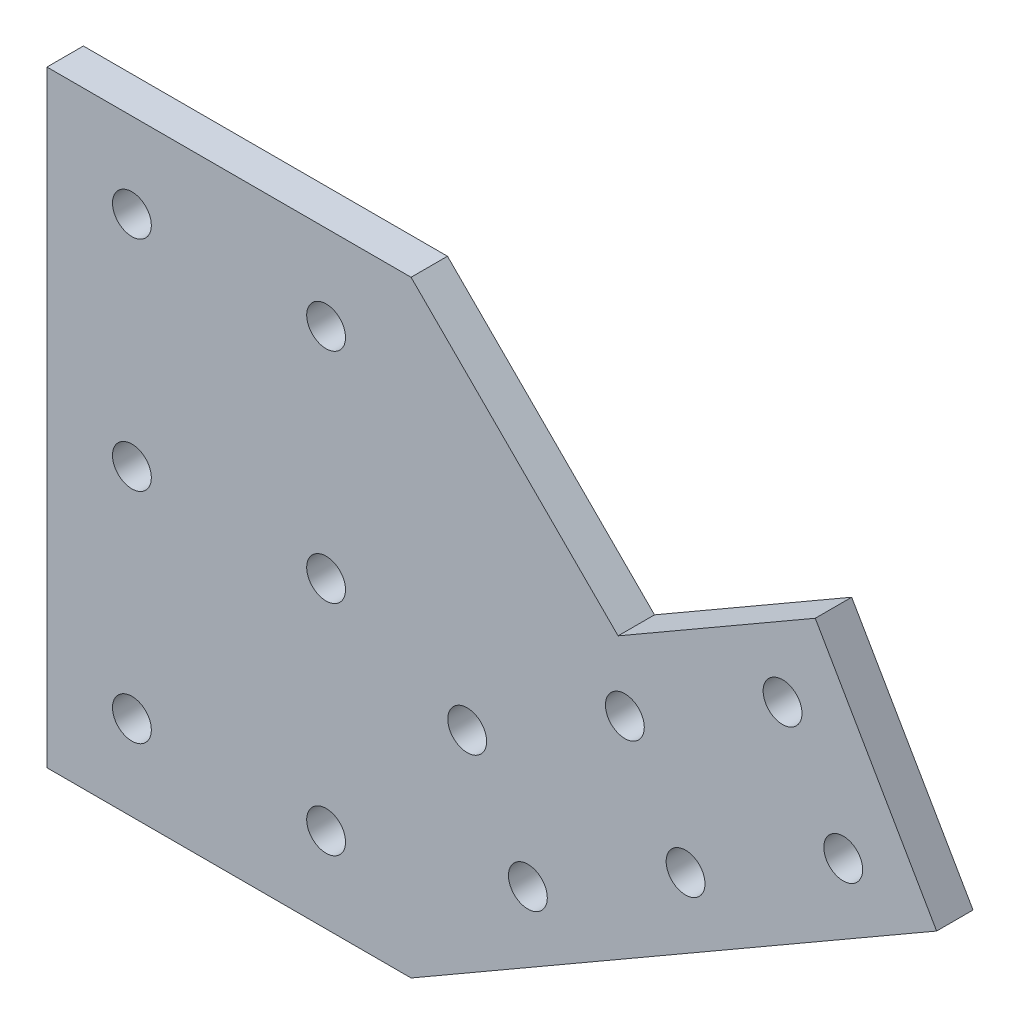
SolidWorks part; units mm, degrees
material "Thornel VCB-20 碳布"
ref_plane "前视基准面" through (0, 0, 0) normal (0, 0, 1) x (1, 0, 0)
ref_plane "上视基准面" through (0, 0, 0) normal (0, 1, 0) x (1, 0, 0)
ref_plane "右视基准面" through (0, 0, 0) normal (1, 0, 0) x (0, 0, -1)
other "Configuration Table"
sketch "草图1" plane through (0, 0, 0) normal (0, 0, 1) x (1, 0, 0)
  line L0 (0, 0) -> (0, 120) construction
  line L1 (0, 120) -> (207.8461, 120) construction
  line L2 (0, 0) -> (207.8461, 120) construction
  line L3 (0, 0) -> (-30, 0)
  line L4 (-30, 0) -> (-30, 50)
  line L5 (-30, 50) -> (0, 50)
  line L6 (0, 50) -> (17.0577, 32.9423)
  line L7 (17.0577, 32.9423) -> (33.3013, 42.3205)
  line L8 (33.3013, 42.3205) -> (43.3013, 25)
  line L9 (43.3013, 25) -> (0, 0)
  dimension "D1" = 60
  dimension "D2" = 240
  dimension "D3" = 20
  dimension "D4" = 30
  dimension "D5" = 50
  dimension "D6" = 50
  dimension "D7" = 45
extrude "凸台-拉伸1" add sketch "草图1" along normal blind 3
sketch "草图2" plane through (0, 0, 3) normal (0, 0, 1) x (1, 0, 0)
  line L0 (0, 50) -> (0, 0) construction
  line L1 (17.0577, 32.9423) -> (0, 23.094) construction
  line L2 (-30, 50) -> (-30, 0) construction
  line L3 (-23, 43) -> (-7, 43) construction
  line L4 (-23, 43) -> (-23, 7) construction
  line L5 (-23, 7) -> (-7, 7) construction
  line L6 (-7, 43) -> (-7, 7) construction
  line L7 (0, 50) -> (-30, 50) construction
  line L10 (0, 0) -> (43.3013, 25) construction
  line L11 (30.6051, 34.9904) -> (35.6051, 26.3301) construction
  line L12 (35.6051, 26.3301) -> (9.6244, 11.3301) construction
  line L13 (9.6244, 11.3301) -> (4.6244, 19.9904) construction
  line L14 (4.6244, 19.9904) -> (30.6051, 34.9904) construction
  line L15 (43.3013, 25) -> (33.3013, 42.3205) construction
  circle A0 centre (-23, 43) radius 1.6
  circle A1 centre (-7, 43) radius 1.6
  circle A2 centre (-23, 7) radius 1.6
  circle A3 centre (-7, 7) radius 1.6
  circle A4 centre (-23, 25) radius 1.6
  circle A5 centre (-7, 25) radius 1.6
  circle A6 centre (30.6051, 34.9904) radius 1.6
  circle A7 centre (35.6051, 26.3301) radius 1.6
  circle A8 centre (22.6147, 18.8301) radius 1.6
  circle A9 centre (17.6147, 27.4904) radius 1.6
  circle A10 centre (4.6244, 19.9904) radius 1.6
  circle A11 centre (9.6244, 11.3301) radius 1.6
  dimension "D5" = 3.2
  dimension "D10" = 3.2
  dimension "D1" = 16
  dimension "D2" = 7
  dimension "D3" = 36
  dimension "D4" = 7
  dimension "D6" = 10
  dimension "D7" = 5
  dimension "D8" = 30
  dimension "D9" = 6
extrude "切除-拉伸1" cut sketch "草图2" against normal through all
